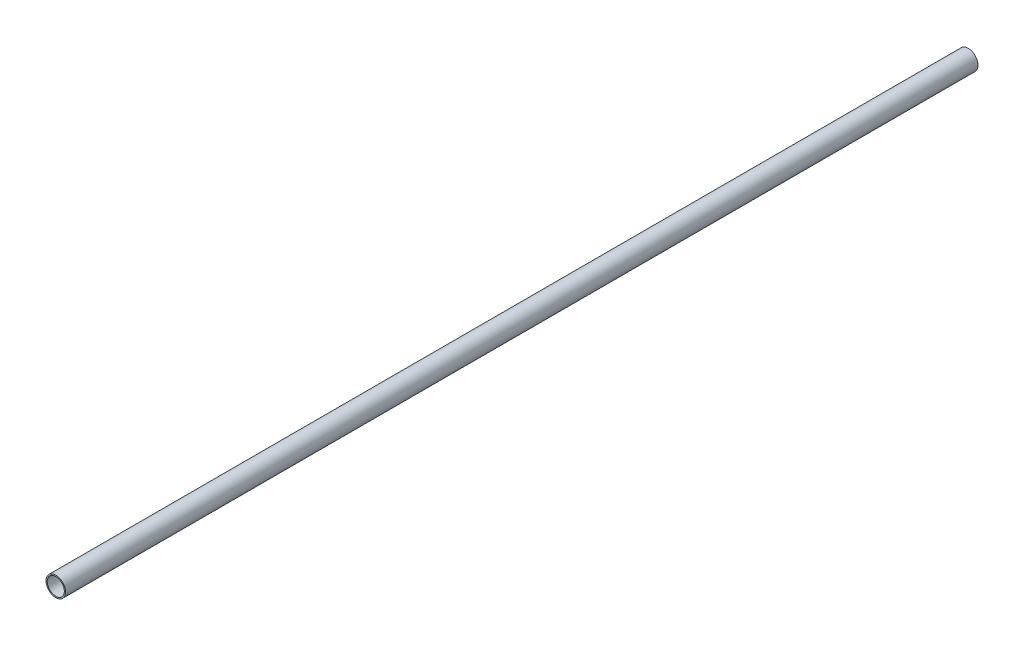
SolidWorks part; units mm, degrees
ref_plane "Plano frontal" through (0, 0, 0) normal (0, 0, 1) x (1, 0, 0)
ref_plane "Plano superior" through (0, 0, 0) normal (0, 1, 0) x (1, 0, 0)
ref_plane "Plano direito" through (0, 0, 0) normal (1, 0, 0) x (0, 0, -1)
sketch "Sketch2" plane through (0, 0, 0) normal (0, 0, 1) x (1, 0, 0)
  circle A0 centre (2449.7201, -5187.0074) radius 24.125
  circle A1 centre (2449.7201, -5187.0074) radius 21.075
  dimension "D1" = 3.05
extrude "Boss-Extrude1" add sketch "Sketch2" along normal blind 2250
